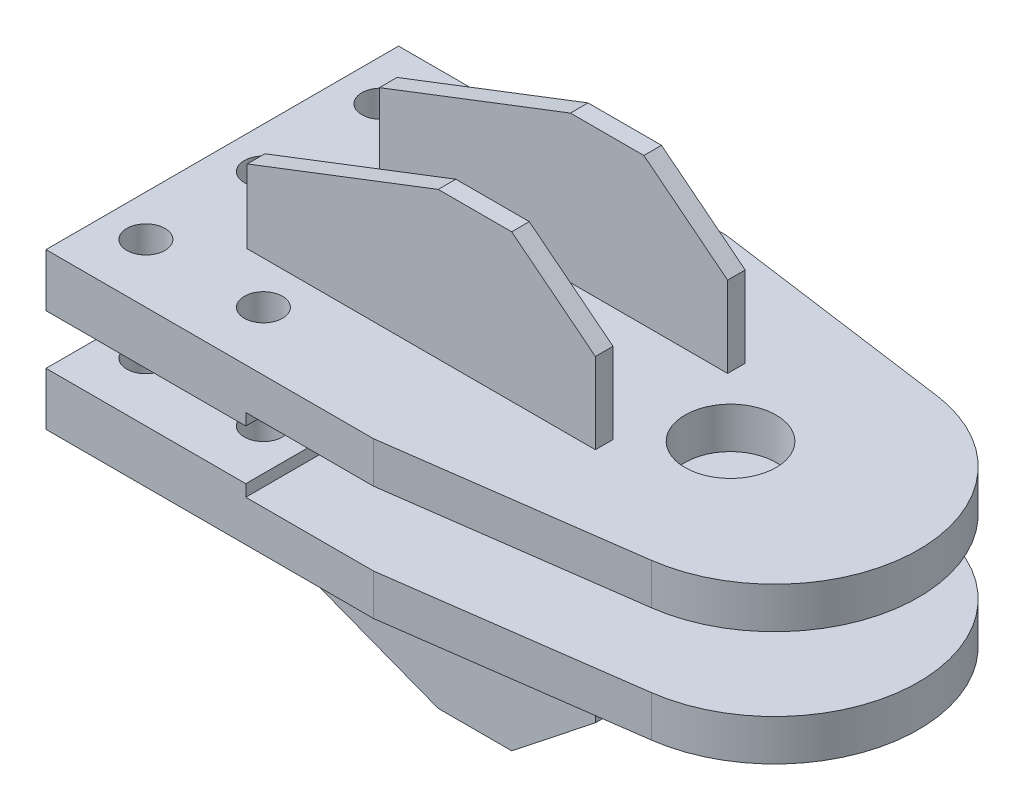
SolidWorks part; units mm, degrees
ref_plane "前视基准面" through (0, 0, 0) normal (0, 0, 1) x (1, 0, 0)
ref_plane "上视基准面" through (0, 0, 0) normal (0, 1, 0) x (1, 0, 0)
ref_plane "右视基准面" through (0, 0, 0) normal (1, 0, 0) x (0, 0, -1)
sketch "草图1" plane through (0, 0, 0) normal (0, 1, 0) x (1, 0, 0)
  line L0 (-1000, 0) -> (49000, 0) construction
  line L1 (0, 120) -> (0, -120)
  line L2 (0, 120) -> (223, 120)
  line L3 (223, 120) -> (389.3726, 97.0833)
  line L4 (0, -120) -> (223, -120)
  line L5 (223, -120) -> (389.3726, -97.0833)
  circle A0 centre (346, 0) radius 31
  arc A1 (389.3726, -97.0833) -> (389.3726, 97.0833) centre (376, 0) ccw
  circle A2 centre (28, 80) radius 13
  circle A3 centre (28, 0) radius 13
  circle A4 centre (28, -80) radius 13
  circle A5 centre (108, 80) radius 13
  circle A6 centre (108, 0) radius 13
  circle A7 centre (108, -80) radius 13
  dimension "D2" = 62
  dimension "D3" = 98
  dimension "D11" = 26
  dimension "D1" = 346
  dimension "D4" = 240
  dimension "D5" = 223
  dimension "D6" = 30
  dimension "D7" = 28
  dimension "D8" = 80
  dimension "D9" = 80
  dimension "D10" = 80
extrude "凸台-拉伸1" add sketch "草图1" along normal blind 28
sketch "草图2" plane through (0, 28, 0) normal (0, 1, 0) x (1, 0, 0)
  line L0 (-1000, 0) -> (49000, 0) construction
  line L1 (68, 51) -> (305, 51)
  line L2 (68, 51) -> (68, 39)
  line L3 (68, 39) -> (305, 39)
  line L4 (305, 51) -> (305, 39)
  line L5 (68, -39) -> (305, -39)
  line L6 (68, -39) -> (68, -51)
  line L7 (68, -51) -> (305, -51)
  line L8 (305, -39) -> (305, -51)
  line L9 (0, 120) -> (0, -120) construction
  dimension "D1" = 78
  dimension "D2" = 12
  dimension "D3" = 68
  dimension "D4" = 237
extrude "凸台-拉伸2" add sketch "草图2" along normal blind 100
sketch "草图3" plane through (0, 0, -51) normal (0, 0, -1) x (1, 0, 0)
  line L0 (305, -128) -> (305, -83)
  line L1 (305, -128) -> (305, -28) construction
  line L2 (305, -83) -> (248, -128)
  line L3 (305, -128) -> (68, -128) construction
  line L4 (248, -128) -> (305, -128)
  line L5 (68, -128) -> (68, -78)
  line L6 (68, -128) -> (68, -28) construction
  line L7 (68, -78) -> (198, -128)
  line L8 (198, -128) -> (68, -128)
  line L9 (305, -28) -> (68, -28) construction
  line L10 (389.3726, -28) -> (223, -28) construction
  dimension "D1" = 50
  dimension "D2" = 130
  dimension "D3" = 57
  dimension "D4" = 55
extrude "切除-拉伸1" cut sketch "草图3" against normal through all
sketch "草图4" plane through (0, 0, 0) normal (0, -1, 0) x (1, 0, 0)
  line L0 (223, -120) -> (0, -120) construction
  line L1 (0, 120) -> (136, 120)
  line L2 (0, 120) -> (0, -120)
  line L3 (0, -120) -> (136, -120)
  line L4 (136, 120) -> (136, -120)
  line L5 (68, -1027.0396) -> (68, 48972.9604) construction
  circle A0 centre (28, 80) radius 13 construction
  circle A1 centre (108, 80) radius 13 construction
  circle A2 centre (28, 80) radius 13
  circle A3 centre (108, 80) radius 13
  circle A4 centre (108, 0) radius 13
  circle A5 centre (28, 0) radius 13
  circle A6 centre (28, -80) radius 13
  circle A7 centre (108, -80) radius 13
  circle A8 centre (28, 0) radius 13 construction
  circle A9 centre (108, 0) radius 13 construction
  circle A10 centre (28, -80) radius 13 construction
  circle A11 centre (108, -80) radius 13 construction
extrude "凸台-拉伸3" add sketch "草图4" along normal blind 8
ref_plane "基准面1" through (0, -25, 0) normal (0, 1, 0) x (1, 0, 0)
mirror "镜向1" about plane through (0, -25, 0) normal (0, 1, 0) of bodies 110 108
